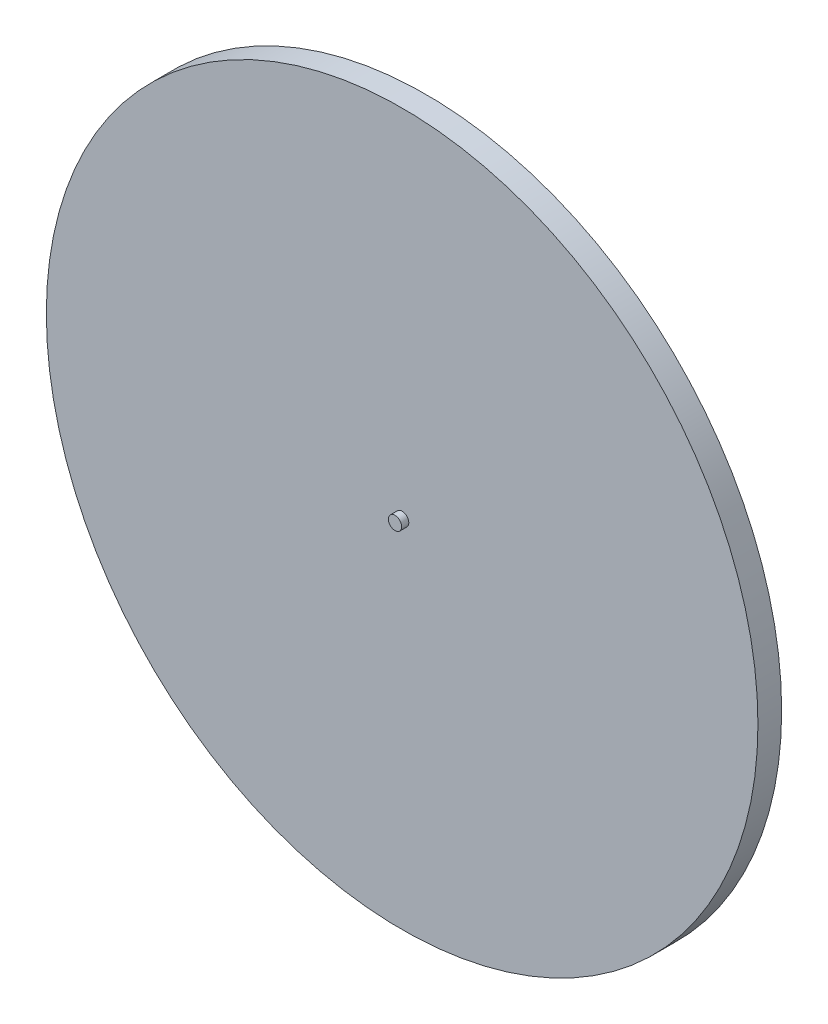
SolidWorks part; units mm, degrees
ref_plane "前视基准面" through (0, 0, 0) normal (0, 0, 1) x (1, 0, 0)
ref_plane "上视基准面" through (0, 0, 0) normal (0, 1, 0) x (1, 0, 0)
ref_plane "右视基准面" through (0, 0, 0) normal (1, 0, 0) x (0, 0, -1)
sketch "草图1" plane through (0, 0, 0) normal (0, 0, 1) x (1, 0, 0)
  circle A0 centre (0, 0) radius 2.8
extrude "凸台-拉伸1" add sketch "草图1" along normal blind 3
sketch "草图2" plane through (0, 0, 0) normal (0, 0, -1) x (-1, 0, 0)
  circle A0 centre (0, 0) radius 150
extrude "凸台-拉伸2" add sketch "草图2" along normal blind 10
